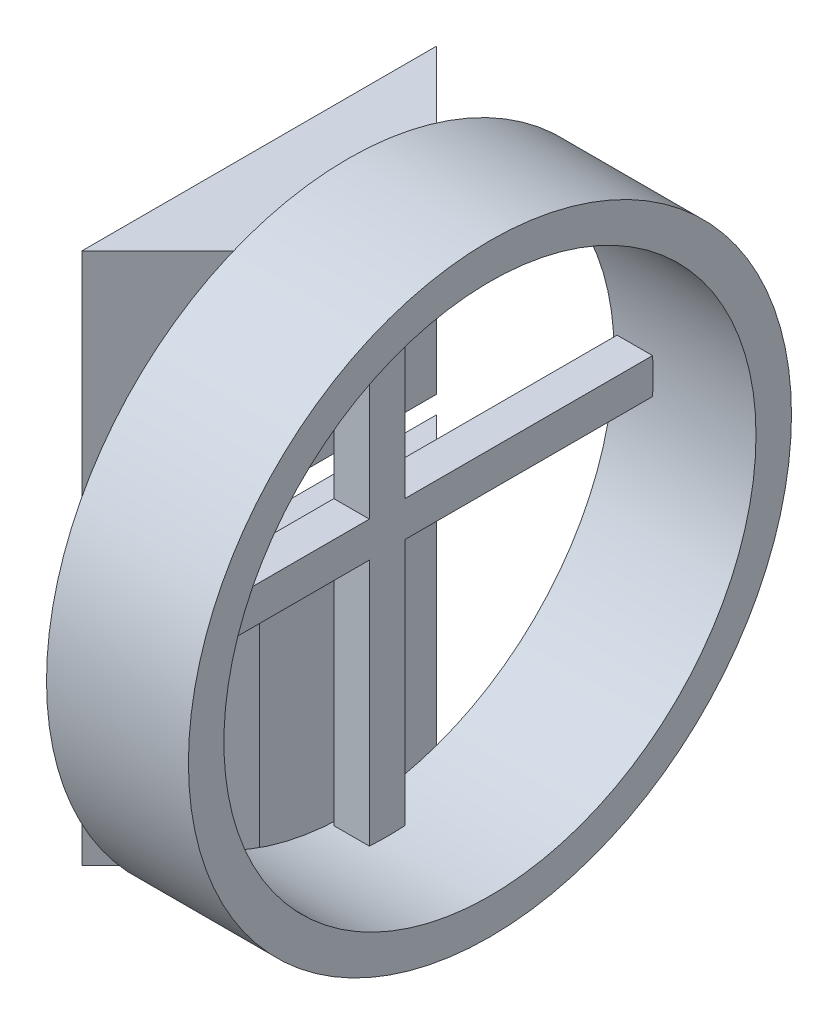
SolidWorks part; units mm, degrees
ref_plane "Front Plane" through (0, 0, 0) normal (0, 0, 1) x (1, 0, 0)
ref_plane "Top Plane" through (0, 0, 0) normal (0, 1, 0) x (1, 0, 0)
ref_plane "Right Plane" through (0, 0, 0) normal (1, 0, 0) x (0, 0, -1)
sketch "Sketch3" plane through (0, 0, 0) normal (0, 1, 0) x (1, 0, 0)
  line L0 (-12.5, 0) -> (12.5, 0) construction
  line L5 (-9.5, 12.5) -> (-2.5, 12.5)
  line L6 (0, -12.5) -> (0, 12.5) construction
  line L11 (-2.5, 12.5) -> (2.5, 12.5)
  line L12 (2.5, 12.5) -> (9.5, 12.5)
  line L13 (12.5, 9.5) -> (12.5, 2.5)
  line L14 (12.5, 2.5) -> (12.5, -2.5)
  line L15 (12.5, -2.5) -> (12.5, -9.5)
  line L16 (9.5, -12.5) -> (2.5, -12.5)
  line L17 (2.5, -12.5) -> (-2.5, -12.5)
  line L18 (-2.5, -12.5) -> (-9.5, -12.5)
  line L19 (-12.5, -9.5) -> (-12.5, -2.5)
  line L20 (-12.5, -2.5) -> (-12.5, 2.5)
  line L21 (-12.5, 2.5) -> (-12.5, 9.5)
  line L22 (-12.5, -2.5) -> (-10, -5)
  line L23 (-10, -5) -> (-10, 5)
  line L24 (-10, 5) -> (-12.5, 2.5)
  line L25 (-2.5, 12.5) -> (-5, 10)
  line L26 (-5, 10) -> (5, 10)
  line L27 (5, 10) -> (2.5, 12.5)
  line L28 (12.5, 2.5) -> (10, 5)
  line L29 (10, 5) -> (10, -5)
  line L30 (10, -5) -> (12.5, -2.5)
  line L31 (-2.5, -12.5) -> (-5, -10)
  line L32 (-5, -10) -> (5, -10)
  line L33 (5, -10) -> (2.5, -12.5)
  line L34 (-7.5, 5) -> (-5, 7.5)
  line L39 (-5, 7.5) -> (5, 7.5)
  line L40 (5, 7.5) -> (7.5, 5)
  line L41 (7.5, 5) -> (7.5, -5)
  line L42 (7.5, -5) -> (5, -7.5)
  line L43 (5, -7.5) -> (-5, -7.5)
  line L44 (-5, -7.5) -> (-7.5, -5)
  line L45 (-7.5, -5) -> (-7.5, 5)
  arc A0 (-9.5, -12.5) -> (-12.5, -9.5) centre (-9.5, -9.5) cw
  arc A1 (12.5, -9.5) -> (9.5, -12.5) centre (9.5, -9.5) cw
  arc A2 (9.5, 12.5) -> (12.5, 9.5) centre (9.5, 9.5) cw
  arc A3 (-9.5, 12.5) -> (-12.5, 9.5) centre (-9.5, 9.5) ccw
  point P2 (0, 0)
  point P6 (0, 0)
  point P26 (0, 0)
  point P39 (-7.2824, 5.6435)
  point P44 (-7.5, 0)
  point P45 (-7.1955, 5)
  point P46 (-7.4281, -5)
  point P47 (-12.5, 0)
  point P53 (-12.7916, 0.0384)
  dimension "D3" = 3
  dimension "D1" = 25
  dimension "D2" = 5
  dimension "D4" = 2.5
  dimension "D5" = 45
  dimension "D6" = 2.5
  dimension "D7" = 2.5
extrude "Boss-Extrude1" add sketch "Sketch3" along normal blind 15 contours L29 L30 L14 L28
sketch "Sketch4" plane through (12.5, 0, 0) normal (1, 0, 0) x (0, 0, -1)
  line L0 (0, 0) -> (0, 15) construction
  line L1 (2.5, 15) -> (-2.5, 15) construction
  circle A0 centre (0, 7.5) radius 7.5
  dimension "D1" = 15
extrude "Extrude-Thin1" add sketch "Sketch4" along normal blind 4 separate body thin
sketch "Sketch7" plane through (12.5, 0, 0) normal (1, 0, 0) x (0, 0, -1)
  line L0 (0, 0) -> (0, 15) construction
  line L1 (2.5, 15) -> (-2.5, 15) construction
  line L2 (0, 7.5) -> (8.0364, 7.5)
  line L3 (0, 7.5) -> (-8.0364, 7.5)
  point P7 (-8.0364, 2.5)
extrude "Extrude-Thin5" add sketch "Sketch7" along normal blind 1 from offset 0.1 thin thin type mid plane wall 1
pattern_circular "CirPattern2" count 4 over 360 about axis through (16.5, 7.5, 0) along (1, 0, 0) of "Extrude-Thin5"
sketch "Sketch9" plane through (0, 0, 0) normal (0, 0, 1) x (1, 0, 0)
  line L0 (10, 15) -> (10, 0) construction
  line L1 (7.5, 9) -> (12.5, 9)
  line L2 (7.5, 9) -> (7.5, 6)
  line L3 (7.5, 6) -> (12.5, 6)
  line L4 (12.5, 9) -> (12.5, 6)
  line L5 (7.5, 9) -> (12.5, 6) construction
  line L6 (7.5, 6) -> (12.5, 9) construction
  line L7 (12.5, 15) -> (12.5, 0) construction
  point P0 (10, 7.5)
  dimension "D1" = 3
extrude "Cut-Extrude2" cut sketch "Sketch9" against normal through all both and the other way through all
